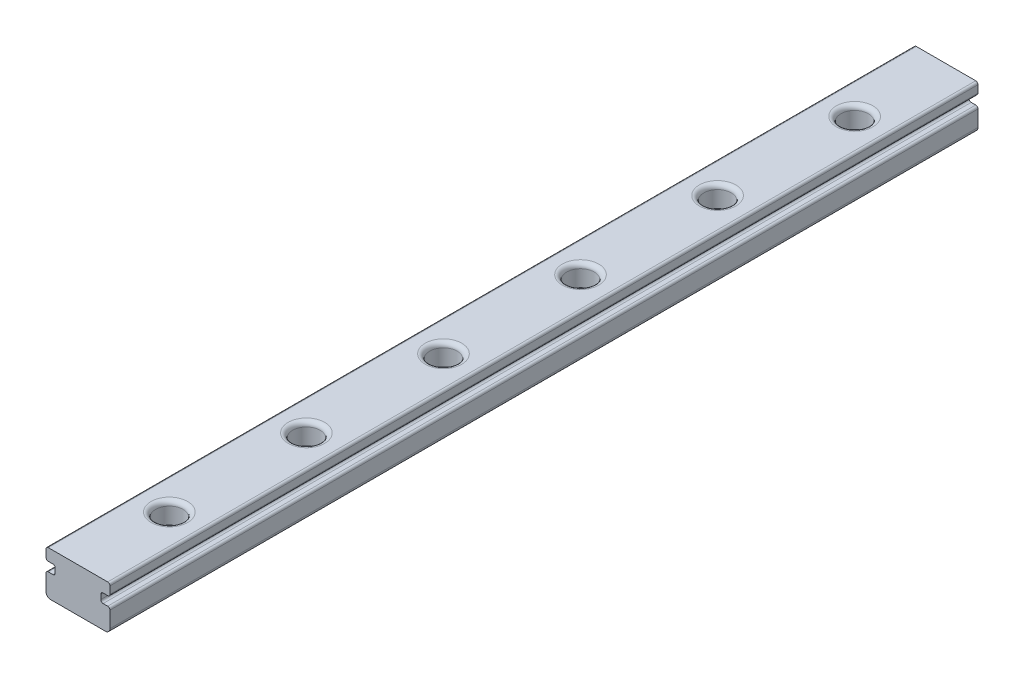
SolidWorks part; units mm, degrees
material "201 退火不锈钢 (SS)"
ref_plane "前视基准面" through (0, 0, 0) normal (0, 0, 1) x (1, 0, 0)
ref_plane "上视基准面" through (0, 0, 0) normal (0, 1, 0) x (1, 0, 0)
ref_plane "右视基准面" through (0, 0, 0) normal (1, 0, 0) x (0, 0, -1)
sketch "草图1" plane through (0, 0, 0) normal (0, 0, 1) x (1, 0, 0)
  line L0 (0, 0) -> (7, 0)
  line L1 (0, 3.5) -> (0, 4.8)
  line L2 (0, 4.8) -> (7, 4.8)
  line L3 (7, 4.8) -> (7, 3.5)
  line L4 (0, 4.8) -> (0, 3.5)
  line L5 (0, 2.5) -> (1, 2.5)
  line L6 (1, 2.5) -> (1, 3.5)
  line L7 (1, 3.5) -> (0, 3.5)
  line L8 (7, 3.5) -> (6, 3.5)
  line L9 (6, 3.5) -> (6, 2.5)
  line L10 (6, 2.5) -> (7, 2.5)
  line L11 (0, 2.5) -> (0, 0)
  line L12 (7, 2.5) -> (7, 0)
extrude "凸台-拉伸1" add sketch "草图1" along normal blind 95 contours L12 L10 L9 L8 L3 L2 L1 L7 L6 L5 L11 L0
fillet "圆角1" radius 0.25 10 edges at (7, 2.5, 47.5) (0, 2.5, 47.5) (1, 3.5, 47.5) (1, 2.5, 47.5) (6, 2.5, 47.5) (6, 3.5, 47.5) (7, 4.8, 47.5) (0, 4.8, 47.5) (0, 3.5, 47.5) (7, 3.5, 47.5)
fillet "圆角2" radius 0.5 2 edges at (0, 0, 47.5) (7, 0, 47.5)
sketch "草图2" plane through (0, 4.8, 0) normal (0, 1, 0) x (1, 0, 0)
  line L0 (0.25, 0) -> (6.75, 0) construction
  line L1 (3.5, 0) -> (3.5, -6.7471) construction
  circle A0 centre (3.5, -10) radius 1.5
  dimension "D1" = 3
  dimension "D2" = 10
extrude "切除-拉伸1" cut sketch "草图2" against normal blind 2.3
sketch "草图3" plane through (0, 2.5, 0) normal (0, 1, 0) x (1, 0, 0)
  line L0 (0.5, 0) -> (6.5, 0) construction
  line L1 (3.5, 0) -> (3.5, -4.4975) construction
  circle A1 centre (3.5, -10) radius 1.2
  dimension "D1" = 2.4
  dimension "D2" = 10
extrude "切除-拉伸2" cut sketch "草图3" against normal through all
fillet "圆角3" radius 0.5 1 edges at (3.5, 4.8, 11.5)
pattern_linear "阵列(线性)2" count 6 spacing 15 along (0, 0, 1) of "切除-拉伸1", "切除-拉伸2", "圆角3"
